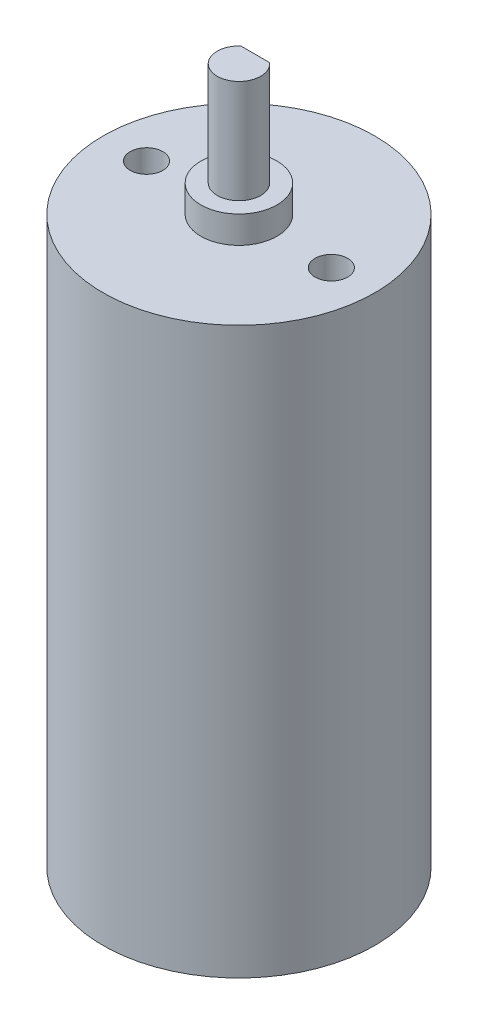
SolidWorks part; units mm, degrees
ref_plane "Front Plane" through (0, 0, 0) normal (0, 0, 1) x (1, 0, 0)
ref_plane "Top Plane" through (0, 0, 0) normal (0, 1, 0) x (1, 0, 0)
ref_plane "Right Plane" through (0, 0, 0) normal (1, 0, 0) x (0, 0, -1)
sketch "Sketch1" plane through (0, 0, 0) normal (0, 1, 0) x (1, 0, 0)
  circle A0 centre (0, 0) radius 12.5
  dimension "D1" = 25
extrude "Boss-Extrude1" add sketch "Sketch1" along normal blind 52
sketch "Sketch2" plane through (0, 52, 0) normal (0, 1, 0) x (1, 0, 0)
  circle A0 centre (0, 0) radius 3.5
  dimension "D1" = 7
extrude "Boss-Extrude2" add sketch "Sketch2" along normal blind 2.5
sketch "Sketch3" plane through (0, 54.5, 0) normal (0, 1, 0) x (1, 0, 0)
  line L0 (0, -2) -> (0, 1.5)
  line L1 (0, 1.5) -> (1.3229, 1.5)
  line L2 (1.3229, 1.5) -> (-1.3229, 1.5)
  arc A0 (-1.3229, 1.5) -> (1.3229, 1.5) centre (0, 0) ccw
  dimension "D1" = 4
  dimension "D2" = 3.5
extrude "Boss-Extrude3" add sketch "Sketch3" along normal blind 9.5 contours L2 A0 L0 | L0 A0 L1
sketch "Sketch4" plane through (0, 52, 0) normal (0, 1, 0) x (1, 0, 0)
  line L0 (-12.5, 0) -> (-10, 0)
  line L1 (-10, 0) -> (-7, 0)
  line L2 (0, 0) -> (0, 5.6219)
  circle A0 centre (0, 0) radius 12.5 construction
  circle A1 centre (-8.5, 0) radius 1.5
  circle A2 centre (8.5, 0) radius 1.5
  dimension "D1" = 2.5
  dimension "D2" = 3
extrude "Cut-Extrude1" cut sketch "Sketch4" against normal blind 8 contours L1 A1 | L1 A1 | A2
